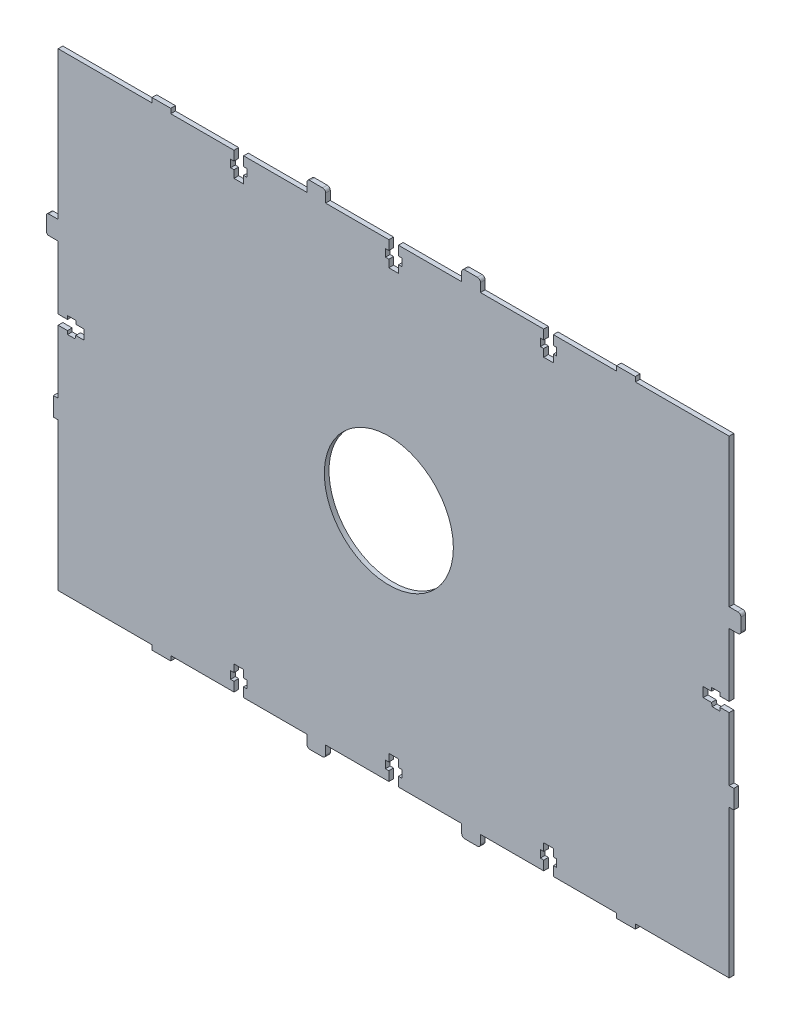
SolidWorks part; units mm, degrees
ref_plane "前视基准面" through (0, 0, 0) normal (0, 0, 1) x (1, 0, 0)
ref_plane "上视基准面" through (0, 0, 0) normal (0, 1, 0) x (1, 0, 0)
ref_plane "右视基准面" through (0, 0, 0) normal (1, 0, 0) x (0, 0, -1)
sketch "草图1" plane through (0, 0, 0) normal (0, 0, 1) x (1, 0, 0)
  line L0 (0, 0) -> (0, -4)
  line L1 (0, -4) -> (-1.45, -4)
  line L2 (-1.45, -4) -> (-1.45, -7.2)
  line L3 (-1.45, -7.2) -> (0, -7.2)
  line L4 (0, -7.2) -> (0, -10.4)
  line L5 (0, -10.4) -> (4.1, -10.4)
  line L6 (4.1, -10.4) -> (4.1, -7.2)
  line L7 (4.1, -7.2) -> (5.55, -7.2)
  line L8 (5.55, -7.2) -> (5.55, -4)
  line L9 (5.55, -4) -> (4.1, -4)
  line L10 (4.1, -4) -> (4.1, 0)
  line L11 (0, 0) -> (-26.95, 0)
  line L12 (-26.95, 0) -> (-26.95, 5)
  line L13 (-26.95, 5) -> (-34.95, 5)
  line L14 (-34.95, 5) -> (-34.95, 0)
  line L15 (2.05, -10.4) -> (2.05, -6.664) construction
  line L16 (-30.95, 5) -> (-30.95, -50.064) construction
  line L17 (-67.45, -4) -> (-66, -4)
  line L18 (-66, -7.2) -> (-67.45, -7.2)
  line L19 (-60.45, -7.2) -> (-61.9, -7.2)
  line L20 (-61.9, -4) -> (-60.45, -4)
  line L21 (-66, -4) -> (-66, 0)
  line L22 (-66, -10.4) -> (-66, -7.2)
  line L23 (-61.9, -10.4) -> (-66, -10.4)
  line L24 (-61.9, -7.2) -> (-61.9, -10.4)
  line L25 (-67.45, -7.2) -> (-67.45, -4)
  line L26 (-60.45, -4) -> (-60.45, -7.2)
  line L27 (-61.9, 0) -> (-61.9, -4)
  line L28 (-61.9, 0) -> (-34.95, 0)
  line L29 (31.05, 5) -> (39.05, 5)
  line L30 (31.05, 0) -> (31.05, 5)
  line L31 (39.05, 5) -> (39.05, 0)
  line L32 (4.1, 0) -> (31.05, 0)
  line L33 (66, 0) -> (39.05, 0)
  line L34 (66, 0) -> (66, -4)
  line L35 (64.55, -4) -> (64.55, -7.2)
  line L36 (71.55, -7.2) -> (71.55, -4)
  line L37 (66, -7.2) -> (66, -10.4)
  line L38 (66, -10.4) -> (70.1, -10.4)
  line L39 (70.1, -10.4) -> (70.1, -7.2)
  line L40 (70.1, -4) -> (70.1, 0)
  line L41 (66, -4) -> (64.55, -4)
  line L42 (64.55, -7.2) -> (66, -7.2)
  line L43 (70.1, -7.2) -> (71.55, -7.2)
  line L44 (71.55, -4) -> (70.1, -4)
  line L45 (68.05, -10.4) -> (68.05, -6.536) construction
  line L46 (70.1, 0) -> (97.05, 0)
  line L47 (132, 0) -> (105.05, 0)
  line L48 (97.05, 5) -> (97.05, 0)
  line L49 (105.05, 0) -> (105.05, 5)
  line L50 (105.05, 5) -> (97.05, 5)
  line L51 (-63.95, -10.4) -> (-63.95, -6.536) construction
  line L52 (-96.95, 5) -> (-96.95, -50.064) construction
  line L53 (-66, 0) -> (-92.95, 0)
  line L54 (-92.95, 5) -> (-92.95, 0)
  line L55 (-100.95, 5) -> (-92.95, 5)
  line L56 (-100.95, 0) -> (-100.95, 5)
  line L57 (-127.9, 0) -> (-100.95, 0)
  line L58 (2.05, -10.4) -> (-140.5, -10.4) construction
  line L59 (-127.9, 0) -> (-140.95, 0)
  line L60 (132, 0) -> (145.05, 0)
  line L63 (145.05, -200) -> (145.05, 0) construction
  line L64 (145.05, -100) -> (115.1583, -100) construction
  line L65 (-127.9, -200) -> (-140.95, -200)
  line L66 (2.05, -189.6) -> (2.05, -193.336) construction
  line L67 (4.1, -196) -> (4.1, -200)
  line L68 (5.55, -196) -> (4.1, -196)
  line L69 (5.55, -192.8) -> (5.55, -196)
  line L70 (4.1, -192.8) -> (5.55, -192.8)
  line L71 (4.1, -189.6) -> (4.1, -192.8)
  line L72 (0, -189.6) -> (4.1, -189.6)
  line L73 (0, -192.8) -> (0, -189.6)
  line L74 (-1.45, -192.8) -> (0, -192.8)
  line L75 (-1.45, -196) -> (-1.45, -192.8)
  line L76 (0, -196) -> (-1.45, -196)
  line L77 (0, -200) -> (0, -196)
  line L78 (132, -200) -> (145.05, -200)
  line L79 (68.05, -189.6) -> (68.05, -193.464) construction
  line L80 (105.05, -205) -> (97.05, -205)
  line L81 (105.05, -200) -> (105.05, -205)
  line L82 (97.05, -205) -> (97.05, -200)
  line L83 (132, -200) -> (105.05, -200)
  line L84 (70.1, -200) -> (97.05, -200)
  line L85 (71.55, -196) -> (70.1, -196)
  line L86 (70.1, -192.8) -> (71.55, -192.8)
  line L87 (64.55, -192.8) -> (66, -192.8)
  line L88 (66, -196) -> (64.55, -196)
  line L89 (70.1, -196) -> (70.1, -200)
  line L90 (70.1, -189.6) -> (70.1, -192.8)
  line L91 (66, -189.6) -> (70.1, -189.6)
  line L92 (66, -192.8) -> (66, -189.6)
  line L93 (71.55, -192.8) -> (71.55, -196)
  line L94 (64.55, -196) -> (64.55, -192.8)
  line L95 (66, -200) -> (66, -196)
  line L96 (66, -200) -> (39.05, -200)
  line L97 (4.1, -200) -> (31.05, -200)
  line L98 (39.05, -205) -> (39.05, -200)
  line L99 (31.05, -200) -> (31.05, -205)
  line L100 (31.05, -205) -> (39.05, -205)
  line L101 (2.05, -189.6) -> (-140.5, -189.6) construction
  line L102 (-96.95, -205) -> (-96.95, -149.936) construction
  line L103 (-63.95, -189.6) -> (-63.95, -193.464) construction
  line L104 (-30.95, -205) -> (-30.95, -149.936) construction
  line L105 (-127.9, -200) -> (-100.95, -200)
  line L106 (-100.95, -200) -> (-100.95, -205)
  line L107 (-100.95, -205) -> (-92.95, -205)
  line L108 (-92.95, -205) -> (-92.95, -200)
  line L109 (-66, -200) -> (-92.95, -200)
  line L110 (-61.9, -200) -> (-34.95, -200)
  line L111 (-61.9, -200) -> (-61.9, -196)
  line L112 (-60.45, -196) -> (-60.45, -192.8)
  line L113 (-67.45, -192.8) -> (-67.45, -196)
  line L114 (-61.9, -192.8) -> (-61.9, -189.6)
  line L115 (-61.9, -189.6) -> (-66, -189.6)
  line L116 (-66, -189.6) -> (-66, -192.8)
  line L117 (-66, -196) -> (-66, -200)
  line L118 (-61.9, -196) -> (-60.45, -196)
  line L119 (-60.45, -192.8) -> (-61.9, -192.8)
  line L120 (-66, -192.8) -> (-67.45, -192.8)
  line L121 (-67.45, -196) -> (-66, -196)
  line L122 (-34.95, -205) -> (-34.95, -200)
  line L123 (-26.95, -205) -> (-34.95, -205)
  line L124 (-26.95, -200) -> (-26.95, -205)
  line L125 (0, -200) -> (-26.95, -200)
  line L126 (145.05, -97.95) -> (141.05, -97.95)
  line L127 (141.05, -97.95) -> (141.05, -96.4903)
  line L128 (141.05, -96.4903) -> (137.5152, -96.4903)
  line L129 (137.5152, -96.4903) -> (137.5152, -97.95)
  line L130 (137.5152, -97.95) -> (133.9804, -97.95)
  line L131 (133.9804, -97.95) -> (133.9804, -102.05)
  line L132 (133.9804, -102.05) -> (137.5152, -102.05)
  line L133 (137.5152, -102.05) -> (137.8502, -103.4708)
  line L134 (137.8502, -103.4708) -> (141.05, -103.5097)
  line L135 (141.05, -103.5097) -> (141.05, -102.05)
  line L136 (141.05, -102.05) -> (145.05, -102.05)
  line L137 (133.9804, -100) -> (145.05, -100) construction
  line L138 (150.05, -67) -> (145.05, -67) construction
  line L139 (145.05, -71) -> (150.05, -71)
  line L140 (150.05, -71) -> (150.05, -63)
  line L141 (150.05, -63) -> (145.05, -63)
  line L142 (150.05, -133) -> (145.05, -133) construction
  line L143 (150.05, -137) -> (145.05, -137)
  line L144 (150.05, -129) -> (150.05, -137)
  line L145 (145.05, -129) -> (150.05, -129)
  line L146 (145.05, -97.95) -> (145.05, -71)
  line L147 (145.05, -102.05) -> (145.05, -129)
  line L148 (145.05, -137) -> (145.05, -200)
  line L149 (145.05, -63) -> (145.05, 0)
  line L150 (-145.95, -133) -> (-140.95, -133) construction
  line L151 (-145.95, -67) -> (-140.95, -67) construction
  line L152 (-140.95, -200) -> (145.05, 0) construction
  line L153 (-106.2114, -194.6101) -> (-127.9883, -163.4691) construction
  line L154 (-140.95, -102.05) -> (-140.95, -129)
  line L155 (-140.95, -97.95) -> (-140.95, -71)
  line L156 (-140.95, -129) -> (-145.95, -129)
  line L157 (-145.95, -129) -> (-145.95, -137)
  line L158 (-145.95, -137) -> (-140.95, -137)
  line L159 (-145.95, -63) -> (-140.95, -63)
  line L160 (-145.95, -71) -> (-145.95, -63)
  line L161 (-140.95, -71) -> (-145.95, -71)
  line L162 (-136.95, -102.05) -> (-140.95, -102.05)
  line L163 (-136.95, -103.5097) -> (-136.95, -102.05)
  line L164 (-133.7502, -103.4708) -> (-136.95, -103.5097)
  line L165 (-133.4152, -102.05) -> (-133.7502, -103.4708)
  line L166 (-129.8804, -102.05) -> (-133.4152, -102.05)
  line L167 (-129.8804, -97.95) -> (-129.8804, -102.05)
  line L168 (-133.4152, -97.95) -> (-129.8804, -97.95)
  line L169 (-133.4152, -96.4903) -> (-133.4152, -97.95)
  line L170 (-136.95, -96.4903) -> (-133.4152, -96.4903)
  line L171 (-136.95, -97.95) -> (-136.95, -96.4903)
  line L172 (-140.95, -97.95) -> (-136.95, -97.95)
  line L173 (-140.95, 0) -> (-140.95, -63)
  line L174 (-140.95, -200) -> (-140.95, -137)
  circle A0 centre (0, -100) radius 27.5
  point P166 (139.4501, -103.4903)
  dimension "D15" = 55
  dimension "D18" = 38
  dimension "D1" = 4.1
  dimension "D2" = 33
  dimension "D3" = 4
  dimension "D4" = 3.2
  dimension "D5" = 7
  dimension "D6" = 200
  dimension "D7" = 5
  dimension "D8" = 286
  dimension "D9" = 4.1
  dimension "D10" = 4
  dimension "D11" = 3.2
  dimension "D12" = 7
  dimension "D13" = 8
  dimension "D14" = 5
  dimension "D16" = 33
  dimension "D17" = 8
extrude "凸台-拉伸1" add sketch "草图1" along normal blind 2 contours L33 L31 L29 L30 L32 L10 L9 L8 L7 L6 L5 L4 L3 L2 L1 L0 L11 L12 L13 L14 L28 L27 L20 L26 L19 L24 L23 L22 L18 L25 L17 L21 L53 L54 L55 L56 L57 L59 L173 L159 L160 L161 L155 L172 L171 L170 L169 L168 L167 L166 L165 L164 L163 L162 L154 L156 L157 L158 L174 L65 L105 L106 L107 L108 L109 L117 L121 L113 L120 L116 L115 L114 L119 L112 L118 L111 L110 L122 L123 L124 L125 L77 L76 L75 L74 L73 L72 L71 L70 L69 L68 L67 L97 L99 L100 L98 L96 L95 L88 L94 L87 L92 L91 L90 L86 L93 L85 L89 L84 L82 L80 L81 L83 L78 L148 L143 L144 L145 L147 L136 L135 L134 L133 L132 L131 L130 L129 L128 L127 L126 L146 L139 L140 L141 L149 L60 L47 L49 L50 L48 L46 L40 L44 L36 L43 L39 L38 L37 L42 L35 L41 L34 | A0
sketch "草图2" plane through (0, -200, 0) normal (0, -1, 0) x (1, 0, 0)
  line L0 (0, 1) -> (4.1, 1)
  line L1 (0, 2) -> (0, 0) construction
  line L2 (4.1, 2) -> (4.1, 0) construction
  circle A0 centre (2.05, 1) radius 2.05
sketch "草图3" plane through (0, 0, 0) normal (0, 1, 0) x (1, 0, 0)
  line L0 (0, -1) -> (4.1, -1)
  line L1 (0, -2) -> (0, 0) construction
  line L2 (4.1, -2) -> (4.1, 0) construction
  circle A0 centre (2.05, -1) radius 2.05
fillet "圆角1" radius 1 4 edges at (-145.95, -137, 1) (-145.95, -129, 1) (-145.95, -63, 1) (-145.95, -71, 1)
fillet "圆角2" radius 1.3 20 edges at (97.05, 5, 1) (105.05, 5, 1) (39.05, 5, 1) (31.05, 5, 1) (-26.95, 5, 1) (-34.95, 5, 1) (-100.95, 5, 1) (-92.95, 5, 1) (-100.95, -205, 1) (-92.95, -205, 1) (-34.95, -205, 1) (-26.95, -205, 1) (31.05, -205, 1) (39.05, -205, 1) (97.05, -205, 1) (105.05, -205, 1) (150.05, -137, 1) (150.05, -129, 1) (150.05, -63, 1) (150.05, -71, 1)
sketch "草图4" plane through (0, 0, 2) normal (0, 0, 1) x (1, 0, 0)
  line L0 (-66, 0) -> (-92.95, 0) construction
  line L1 (-103.3854, 10.2629) -> (-87.2942, 10.2629)
  line L2 (-103.3854, 10.2629) -> (-103.3854, 2)
  line L3 (-103.3854, 2) -> (-87.2942, 2)
  line L4 (-87.2942, 10.2629) -> (-87.2942, 2)
  line L5 (90.8931, 10.2629) -> (110.825, 10.2629)
  line L6 (90.8931, 10.2629) -> (90.8931, 2)
  line L7 (90.8931, 2) -> (110.825, 2)
  line L8 (110.825, 10.2629) -> (110.825, 2)
  line L9 (-104.6148, -202) -> (-90.1272, -202)
  line L10 (-104.6148, -202) -> (-104.6148, -207.89)
  line L11 (-104.6148, -207.89) -> (-90.1272, -207.89)
  line L12 (-90.1272, -202) -> (-90.1272, -207.89)
  line L13 (94.1099, -202) -> (110.825, -202)
  line L14 (94.1099, -202) -> (94.1099, -210.1778)
  line L15 (94.1099, -210.1778) -> (110.825, -210.1778)
  line L16 (110.825, -202) -> (110.825, -210.1778)
  line L17 (145.05, 0) -> (105.05, 0) construction
  line L18 (-66, -200) -> (-92.95, -200) construction
  line L19 (105.05, -200) -> (145.05, -200) construction
  line L20 (-140.95, 0) -> (-140.95, -63) construction
  line L21 (-153.0557, -111.648) -> (-142.95, -111.648)
  line L22 (-153.0557, -111.648) -> (-153.0557, -137.7144)
  line L23 (-153.0557, -137.7144) -> (-142.95, -137.7144)
  line L24 (-142.95, -111.648) -> (-142.95, -137.7144)
  line L25 (147.05, -113.9361) -> (152.7115, -113.9361)
  line L26 (147.05, -113.9361) -> (147.05, -141.3929)
  line L27 (147.05, -141.3929) -> (152.7115, -141.3929)
  line L28 (152.7115, -113.9361) -> (152.7115, -141.3929)
  line L29 (145.05, -63) -> (145.05, 0) construction
  dimension "D1" = 2
  dimension "D2" = 2
  dimension "D3" = 2
  dimension "D4" = 2
  dimension "D5" = 2
  dimension "D6" = 2
extrude "切除-拉伸1" cut sketch "草图4" against normal blind 2
